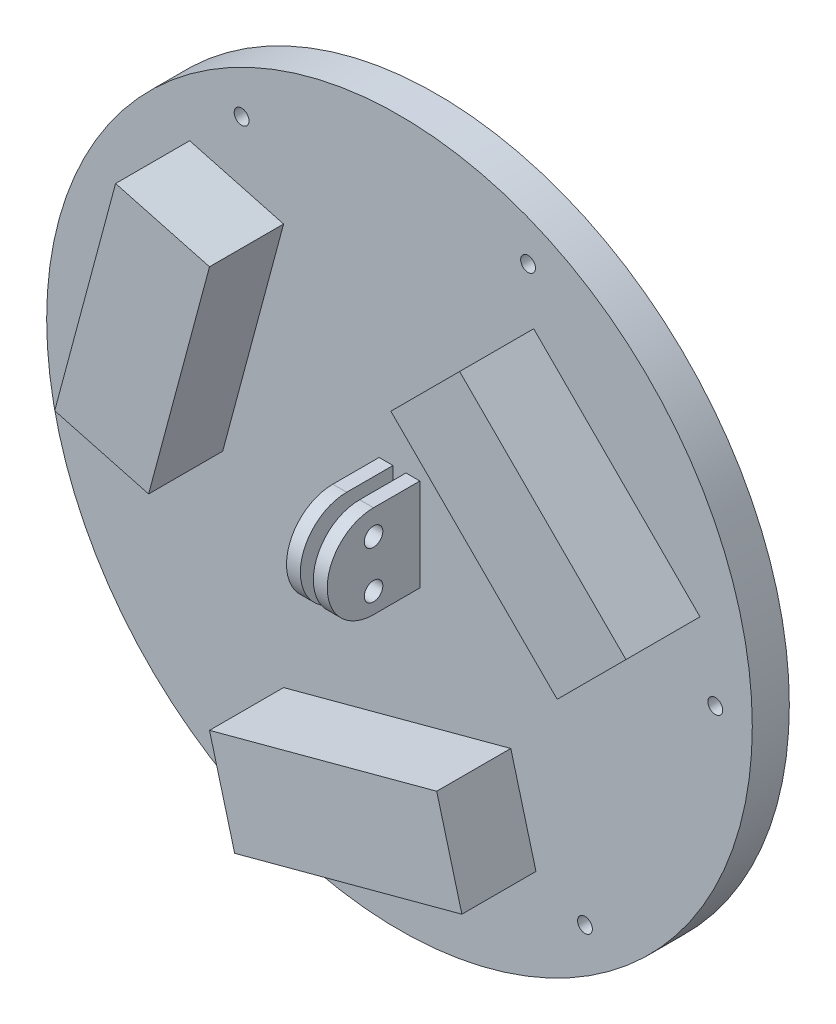
SolidWorks part; units mm, degrees
ref_plane "Front Plane" through (0, 0, 0) normal (0, 0, 1) x (1, 0, 0)
ref_plane "Top Plane" through (0, 0, 0) normal (0, 1, 0) x (1, 0, 0)
ref_plane "Right Plane" through (0, 0, 0) normal (1, 0, 0) x (0, 0, -1)
sketch "Sketch2" plane through (0, 0, 0) normal (0, 0, 1) x (1, 0, 0)
  circle A0 centre (0, 0) radius 38.1
  point P11 (0, 0)
  dimension "D1" = 76.2
extrude "Boss-Extrude1" add sketch "Sketch2" along normal blind 4 contours A0
sketch "Sketch3" plane through (0, 0, 4) normal (0, 0, 1) x (1, 0, 0)
  circle A0 centre (34.1, -0.0857) radius 0.8
  circle A1 centre (-17.05, -29.6172) radius 0.8
  circle A2 centre (-17.05, 29.4457) radius 0.8
  point P8 (0, -0.0857)
  dimension "D1" = 1.6
  dimension "D3" = 34.1
  dimension "D2" = 3
extrude "Cut-Extrude1" cut sketch "Sketch3" against normal blind 6
sketch "Sketch4" plane through (0, 0, 4) normal (0, 0, 1) x (1, 0, 0)
  circle A0 centre (0, 0) radius 0.6
  dimension "D1" = 1.2
extrude "Cut-Extrude2" cut sketch "Sketch4" against normal blind 6
sketch "Sketch5" plane through (0, 0, 4) normal (0, 0, 1) x (1, 0, 0)
  line L1 (0.7, 5) -> (2.2, 5)
  line L2 (0.7, 5) -> (0.7, -5)
  line L3 (0.7, -5) -> (2.2, -5)
  line L4 (2.2, 5) -> (2.2, -5)
  line L5 (-0.7, 5) -> (-2.2, 5)
  line L6 (-0.7, 5) -> (-0.7, -5)
  line L7 (-0.7, -5) -> (-2.2, -5)
  line L8 (-2.2, 5) -> (-2.2, -5)
  dimension "D1" = 10
  dimension "D2" = 1.5
  dimension "D3" = 2.2
  dimension "D4" = 5
  dimension "D5" = 2.2
  dimension "D6" = 5
extrude "Boss-Extrude2" add sketch "Sketch5" along normal blind 10
sketch "Sketch6" plane through (2.2, 0, 0) normal (1, 0, 0) x (0, 0, -1)
  line L0 (-14, -5) -> (-4, -5) construction
  line L1 (-14, 5) -> (-4, 5) construction
  line L2 (-9, 5) -> (-14, 5)
  line L3 (-14, 5) -> (-14, -5)
  line L5 (-14, -5) -> (-9, -5)
  line L6 (-14, 5) -> (-9, 5)
  arc A2 (-9, -5) -> (-9, 5) centre (-9, 0) cw
  point P1 (-9, -5)
  point P2 (-9.1485, 5)
  line M5 (-4, 5) -> (-14, 5)
  line M6 (-14, 5) -> (-14, -5)
  line M7 (-14, -5) -> (-4, -5)
extrude "Cut-Extrude3" cut sketch "Sketch6" against normal through all contours A2 M6 M5 | A2 L3 M7
sketch "Sketch7" plane through (2.2, 0, 0) normal (1, 0, 0) x (0, 0, -1)
  line L1 (-9, 5) -> (-4, 5) construction
  line L2 (-9, -5) -> (-4, -5) construction
  circle A2 centre (-9, 2.3) radius 1
  circle A3 centre (-9, -2.8) radius 1
  dimension "D1" = 2.7
  dimension "D2" = 2.2
  dimension "D4" = 2
extrude "Cut-Extrude4" cut sketch "Sketch7" against normal through all
sketch "Sketch8" plane through (0, 0, 4) normal (0, 0, 1) x (1, 0, 0)
  line L0 (25.0288, 0) -> (32.4534, 7.4246)
  line L1 (25.0288, 0) -> (7.0683, 17.9605)
  line L2 (32.4534, 7.4246) -> (14.4929, 25.3851)
  line L3 (7.0683, 17.9605) -> (14.4929, 25.3851)
  line L4 (0, 0) -> (50000, 0) construction
  line L5 (12.0201, -15.1016) -> (14.7377, -25.2438)
  line L6 (-9.7968, -31.8178) -> (14.7377, -25.2438)
  line L7 (-12.5144, -21.6756) -> (-9.7968, -31.8178)
  line L8 (-12.5144, -21.6756) -> (12.0201, -15.1016)
  line L9 (-19.0884, -2.8589) -> (-29.2306, -0.1413)
  line L10 (-22.6566, 24.3932) -> (-29.2306, -0.1413)
  line L11 (-12.5144, 21.6756) -> (-22.6566, 24.3932)
  line L12 (-12.5144, 21.6756) -> (-19.0884, -2.8589)
  point P17 (0, 0)
  dimension "D1" = 10.5
  dimension "D2" = 25.4
  dimension "D3" = 45
  dimension "D4" = 25.0288
  dimension "D5" = 3
extrude "Boss-Extrude3" add sketch "Sketch8" along normal blind 8
sketch "Sketch10" plane through (0, 0, 4) normal (0, 0, 1) x (1, 0, 0)
  circle A0 centre (13.8868, 31.1443) radius 0.8
  circle A1 centre (20.0284, -27.5984) radius 0.8
  circle A2 centre (-33.9151, -3.5459) radius 0.8
  point P10 (0, 0)
  dimension "D1" = 1.6
  dimension "D2" = 34.1
  dimension "D3" = 3
extrude "Cut-Extrude5" cut sketch "Sketch10" against normal through all
